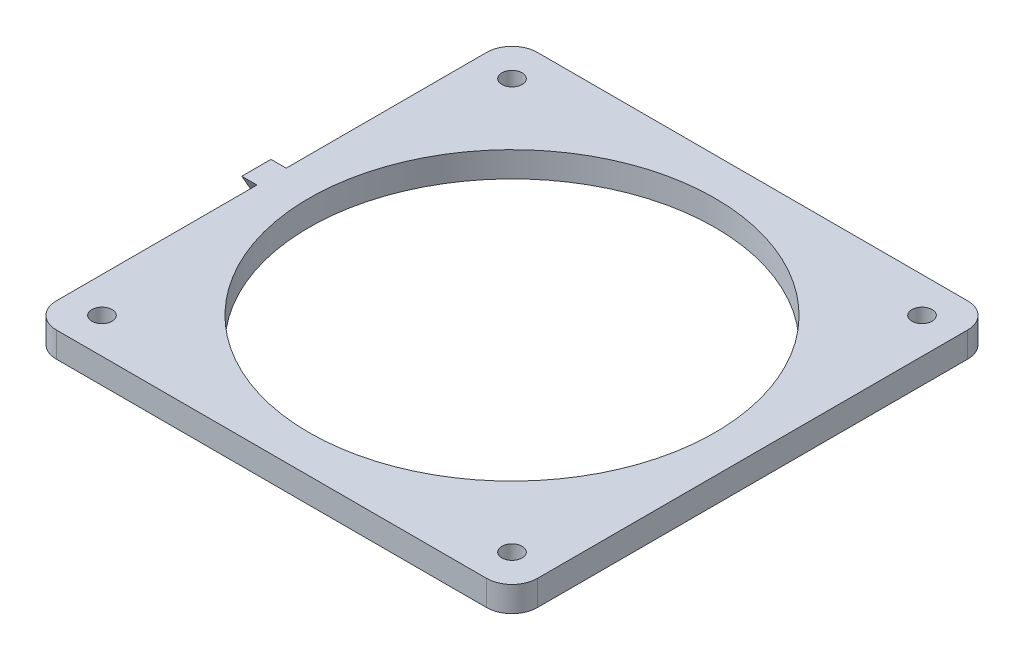
SolidWorks part; units mm, degrees
ref_plane "Front Plane" through (0, 0, 0) normal (0, 0, 1) x (1, 0, 0)
ref_plane "Top Plane" through (0, 0, 0) normal (0, 1, 0) x (1, 0, 0)
ref_plane "Right Plane" through (0, 0, 0) normal (1, 0, 0) x (0, 0, -1)
sketch "Sketch1" plane through (0, 0, 0) normal (0, 1, 0) x (1, 0, 0)
  line L1 (-47.5, -47.5) -> (47.5, -47.5)
  line L2 (-47.5, -47.5) -> (-47.5, 47.5)
  line L3 (-47.5, 47.5) -> (47.5, 47.5)
  line L4 (47.5, -47.5) -> (47.5, 47.5)
  line L5 (-47.5, -47.5) -> (47.5, 47.5) construction
  line L6 (-47.5, 47.5) -> (47.5, -47.5) construction
  line L7 (-40.5, -40.5) -> (40.5, -40.5)
  line L8 (-40.5, -40.5) -> (-40.5, 40.5)
  line L9 (-40.5, 40.5) -> (40.5, 40.5)
  line L10 (40.5, -40.5) -> (40.5, 40.5)
  line L11 (-40.5, -40.5) -> (40.5, 40.5) construction
  line L12 (-40.5, 40.5) -> (40.5, -40.5) construction
  circle A0 centre (0, 0) radius 40.1
  point P0 (0, 0)
  dimension "D3" = 80.2
  dimension "D1" = 95
  dimension "D2" = 95
  dimension "D4" = 81
extrude "Boss-Extrude1" add sketch "Sketch1" along normal blind 5 contours L7 L10 L9 L8 A0 | L1 L4 L3 L2 L10 L7 L8 L9
hole_wizard "Ø4.0mm Dowel Hole1" positions "Sketch2" profile "Sketch4" hole size "Ø4.0" standard "ANSI Metric" end condition through all
sketch "Sketch2" plane through (0, 0, 0) normal (0, -1, 0) x (-1, 0, 0)
  point P0 (40.5, -40.5)
  point P3 (-40.5, -40.5)
  point P6 (-40.5, 40.5)
  point P9 (40.5, 40.5)
sketch "Sketch4" plane through (-40.5, 0, 40.5) normal (1, 0, 0) x (0, 0, -1)
  line L0 (0, 0) -> (0, 5)
  line L1 (0, 5) -> (2, 5)
  line L2 (2, 5) -> (2, 0)
  line L5 (2, 0) -> (0, 0)
  line L11 (0, -6.35) -> (0, 107.95) construction
  dimension "Thru Hole Dia." = 4
  dimension "Thru Hole Depth" = 5
sketch "Sketch5" plane through (-47.5, 0, 0) normal (-1, 0, 0) x (0, 0, 1)
  line L0 (0, 0) -> (-2.8868, 5)
  line L1 (47.5, 0) -> (-47.5, 0) construction
  line L2 (47.5, 5) -> (-47.5, 5) construction
  line L3 (-2.8868, 5) -> (2.8868, 5)
  line L4 (2.8868, 5) -> (0, 0)
  dimension "D1" = 60
  dimension "D2" = 60
extrude "Boss-Extrude2" add sketch "Sketch5" along normal blind 3
fillet "Fillet1" radius 5 4 edges at (-47.5, 2.5, -47.5) (47.5, 2.5, -47.5) (47.5, 2.5, 47.5) (-47.5, 2.5, 47.5)
